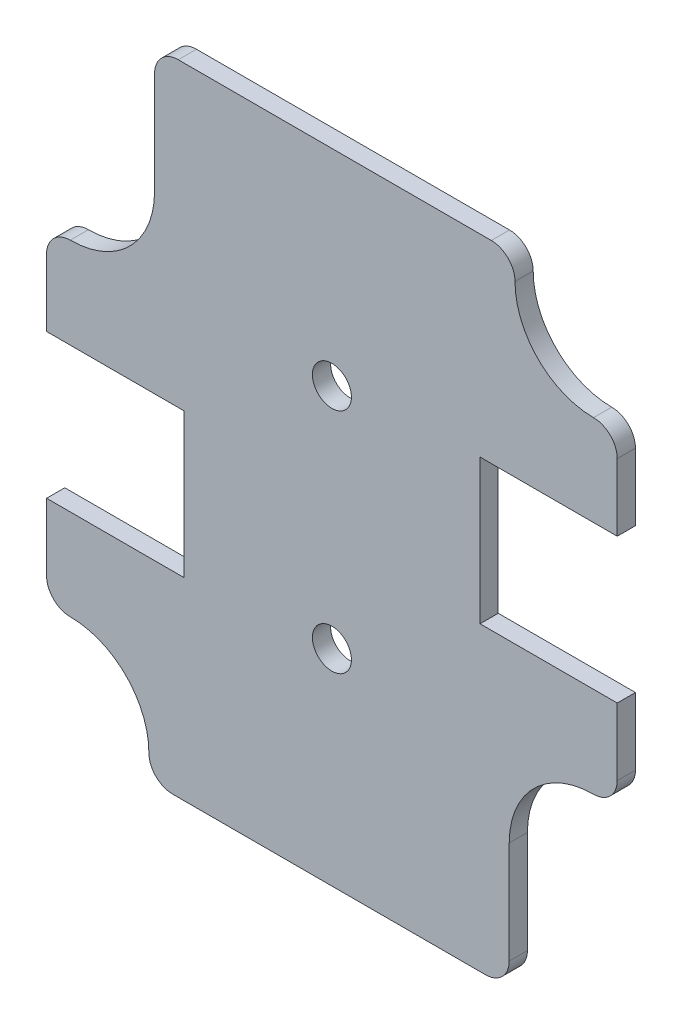
SolidWorks part; units mm, degrees
ref_plane "Front Plane" through (0, 0, 0) normal (0, 0, 1) x (1, 0, 0)
ref_plane "Top Plane" through (0, 0, 0) normal (0, 1, 0) x (1, 0, 0)
ref_plane "Right Plane" through (0, 0, 0) normal (1, 0, 0) x (0, 0, -1)
sketch "Sketch2" plane through (0, 0, 0) normal (0, 0, 1) x (1, 0, 0)
  line L0 (38.6072, 0) -> (11.0828, 0)
  line L1 (0, 11.0828) -> (0, 16.9926)
  line L2 (0, 29.6926) -> (0, 35.6072)
  line L3 (9.5, 45.1068) -> (9.5, 54.102)
  line L4 (11.5828, 56.1848) -> (39.116, 56.1848)
  line L5 (50.19, 45.102) -> (50.19, 39.1922)
  line L6 (50.19, 26.4922) -> (50.19, 20.5828)
  line L7 (40.69, 11.0832) -> (40.69, 2.0828)
  line L8 (0, 29.6926) -> (12.065, 29.6926)
  line L9 (12.065, 29.6926) -> (12.065, 16.9926)
  line L10 (12.065, 16.9926) -> (0, 16.9926)
  line L11 (50.19, 39.1922) -> (38.125, 39.1922)
  line L12 (38.125, 39.1922) -> (38.125, 26.4922)
  line L13 (38.125, 26.4922) -> (50.19, 26.4922)
  arc A0 (9, 2.1) -> (11.0828, 0) centre (11.0914, 2.0914) ccw
  arc A1 (9, 2.1) -> (2.1, 9) centre (2.1, 2.1) ccw
  arc A2 (0, 11.0828) -> (2.1, 9) centre (2.0914, 11.0914) ccw
  arc A3 (2.0832, 37.69) -> (0, 35.6072) centre (2.083, 35.607) ccw
  arc A4 (2.0832, 37.69) -> (9.5, 45.1068) centre (2.0832, 45.1068) ccw
  arc A5 (11.5828, 56.1848) -> (9.5, 54.102) centre (11.5828, 54.102) ccw
  arc A6 (41.1988, 54.102) -> (39.116, 56.1848) centre (39.116, 54.102) ccw
  arc A7 (41.1988, 54.102) -> (48.1072, 47.1848) centre (48.1116, 54.0976) ccw
  arc A8 (50.19, 45.102) -> (48.1072, 47.1848) centre (48.1072, 45.102) ccw
  arc A9 (48.1068, 18.5) -> (50.19, 20.5828) centre (48.107, 20.583) ccw
  arc A10 (48.1068, 18.5) -> (40.69, 11.0832) centre (48.1068, 11.0832) ccw
  arc A11 (38.6072, 0) -> (40.69, 2.0828) centre (38.6072, 2.0828) ccw
  circle A12 centre (25.0952, 18.0848) radius 1.7145
  circle A13 centre (25.0952, 38.1) radius 1.7145
extrude "Boss-Extrude1" add sketch "Sketch2" along normal blind 1.6002 contours L0 A11 L7 A10 A9 L6 L13 L12 L11 L5 A8 A7 A6 L4 A5 L3 A4 A3 L2 L8 L9 L10 L1 A2 A1 A0 A13 A12
